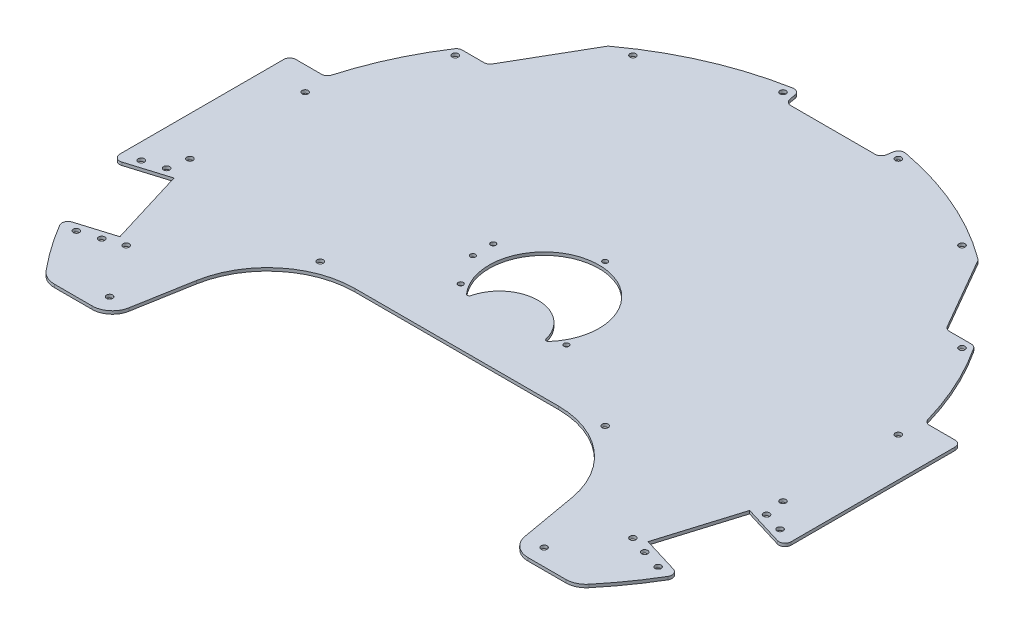
SolidWorks part; units mm, degrees
material "3.0205 (EN-AW 1200)"
ref_plane "Plan de face" through (0, 0, 0) normal (0, 0, 1) x (1, 0, 0)
ref_plane "Plan de dessus" through (0, 0, 0) normal (0, 1, 0) x (1, 0, 0)
ref_plane "Plan de droite" through (0, 0, 0) normal (1, 0, 0) x (0, 0, -1)
sketch "Esquisse1" plane through (0, 0, 0) normal (0, 1, 0) x (1, 0, 0)
  line L2 (0, 0) -> (165, 0) construction
  line L4 (165, -54.557) -> (165, 55.2417)
  line L5 (-165, 55.2417) -> (-104.5177, 160)
  line L6 (-165, -54.557) -> (-165, 55.2417)
  line L9 (0, 160) -> (0, 0) construction
  line L12 (-104.5177, 160) -> (104.5177, 160)
  line L13 (165, 55.2417) -> (104.5177, 160)
  arc A0 (-165, -54.557) -> (-112.9493, -132.0754) centre (0, 0) ccw
  circle A1 centre (158.5, 53.5) radius 6.5 construction
  circle A2 centre (-158.5, 53.5) radius 6.5 construction
  circle A3 centre (158.5, -53.5) radius 6.5 construction
  circle A4 centre (-158.5, -53.5) radius 6.5 construction
  arc A5 (-112.9493, -132.0754) -> (112.9493, -132.0754) centre (0, 355) ccw
  arc A6 (112.9493, -132.0754) -> (165, -54.557) centre (0, 0) ccw
  point P21 (0, -145)
  dimension "D2" = 145
  dimension "D13" = 225.8987
  dimension "D16" = 500
  dimension "D9" = 13
  dimension "D12" = 317
  dimension "D15" = 107
  dimension "D4" = 60
  dimension "D5" = 209.0355
  dimension "D6" = 330
  dimension "D7" = 120.9645
  dimension "D8" = 109.7986
  dimension "D10" = 93.3723
  dimension "D11" = 160
extrude "Boss.-Extru.1" add sketch "Esquisse1" along normal blind 1.5
sketch "Esquisse2" plane through (0, 1.5, 0) normal (0, 1, 0) x (1, 0, 0)
  line L0 (0, 0) -> (0, -145) construction
  line L1 (-92.3467, -78.5331) -> (-104.0666, -145)
  line L2 (-50, -43) -> (50, -43)
  line L3 (92.3467, -78.5331) -> (104.0666, -145)
  line L4 (-104.0666, -145) -> (104.0666, -145)
  line L5 (141.4855, -40.4511) -> (166.9803, -48.2251)
  line L6 (141.4855, -40.4511) -> (129.8189, -78.7119)
  line L7 (166.9803, -48.2251) -> (155.3137, -86.4859)
  line L8 (129.8189, -78.7119) -> (155.3137, -86.4859)
  line L9 (151.0507, -43.3677) -> (145.2174, -62.4981) construction
  line L10 (145.2174, -62.4981) -> (135.6522, -59.5815) construction
  line L11 (-141.4855, -40.4511) -> (-166.9803, -48.2251)
  line L12 (-166.9803, -48.2251) -> (-155.3137, -86.4859)
  line L13 (-141.4855, -40.4511) -> (-129.8189, -78.7119)
  line L14 (-129.8189, -78.7119) -> (-155.3137, -86.4859)
  line L15 (-106.7731, -106.7731) -> (0, 0) construction
  line L16 (165, -54.557) -> (165, 55.2417) construction
  arc A0 (18.8162, -19.3636) -> (-18.8162, -19.3636) centre (0, -22) ccw
  arc A1 (-50, -43) -> (-92.3467, -78.5331) centre (-50, -86) ccw
  arc A2 (-112.9493, -132.0754) -> (112.9493, -132.0754) centre (0, 355) ccw construction
  arc A3 (50, -43) -> (92.3467, -78.5331) centre (50, -86) cw
  arc A4 (18.8162, -19.3636) -> (-18.8162, -19.3636) centre (0, 0) ccw
  circle A5 centre (-106.7731, -106.7731) radius 1.5
  circle A6 centre (143, -86.913) radius 1.5
  circle A7 centre (133.4348, -83.9963) radius 1.5
  circle A8 centre (147.4348, -38.0833) radius 1.5
  circle A9 centre (157, -41) radius 1.5
  arc A10 (112.9493, -132.0754) -> (165, -54.557) centre (0, 0) ccw construction
  circle A11 centre (-147.4348, -38.0833) radius 1.5
  circle A12 centre (-157, -41) radius 1.5
  circle A13 centre (-143, -86.913) radius 1.5
  circle A14 centre (-133.4348, -83.9963) radius 1.5
  circle A15 centre (106.7731, -106.7731) radius 1.5
  dimension "D1" = 19
  dimension "D2" = 22
  dimension "D3" = 86
  dimension "D4" = 100
  dimension "D5" = 54
  dimension "D8" = 10
  dimension "D9" = 48
  dimension "D10" = 10
  dimension "D14" = 41
  dimension "D15" = 3
  dimension "D6" = 86
  dimension "D7" = 20
  dimension "D12" = 3
  dimension "D13" = 8
  dimension "D18" = 22
  dimension "D11" = 40
  dimension "D16" = 151
  dimension "D17" = 45
extrude "Enlèv. mat.-Extru.1" cut sketch "Esquisse2" against normal blind 10
sketch "Esquisse3" plane through (0, 1.5, 0) normal (0, 1, 0) x (1, 0, 0)
  line L1 (-130.2938, -115) -> (130.2938, -115)
  line L2 (-130.2938, -115) -> (-130.2938, -134.4427)
  line L3 (-130.2938, -134.4427) -> (130.2938, -134.4427)
  line L4 (130.2938, -115) -> (130.2938, -134.4427)
  arc A0 (-151.4132, -85.2965) -> (-112.9493, -132.0754) centre (0, 0) ccw construction
  arc A1 (112.9493, -132.0754) -> (151.4132, -85.2965) centre (0, 0) ccw construction
  circle A2 centre (-106.7731, -106.7731) radius 1.5 construction
  dimension "D1" = 8.2269
  dimension "D2" = 115
extrude "Enlèv. mat.-Extru.2" cut sketch "Esquisse3" against normal through all
fillet "Congé1" radius 10 8 edges at (130.2938, 0.75, 115) (98.7768, 0.75, 115) (-98.7768, 0.75, 115) (-130.2938, 0.75, 115) (165, 0.75, -55.2417) (104.5177, 0.75, -160) (-104.5177, 0.75, -160) (-165, 0.75, -55.2417)
fillet "Congé2" radius 1 2 edges at (18.8162, 0.75, 19.3636) (-18.8162, 0.75, 19.3636)
sketch "Esquisse4" plane through (0, 1.5, 0) normal (0, 1, 0) x (1, 0, 0)
  line L0 (0, 0) -> (-124.5426, -80.8789) construction
  line L1 (0, 0) -> (-145.7716, -28.3351) construction
  line L2 (0, 0) -> (-165, 0) construction
  line L3 (-165, 52.5622) -> (-165, -47.6212) construction
  circle A0 centre (-124.5426, -80.8789) radius 1.5
  circle A1 centre (-145.7716, -28.3351) radius 1.5
  circle A2 centre (-145.7716, 28.3351) radius 1.5
  circle A3 centre (-124.5426, 80.8789) radius 1.5
  dimension "D1" = 148.5
  dimension "D2" = 3
  dimension "D4" = 22
  dimension "D5" = 11
  dimension "D3" = 4
extrude "Enlèv. mat.-Extru.3" cut sketch "Esquisse4" against normal through all
pattern_circular "Répétition circulaire1" count 3 every 90 about axis through (0, 0, 0) along (0, 1, 0) of "Enlèv. mat.-Extru.3"
sketch "Esquisse5" plane through (0, 1.5, 0) normal (0, 1, 0) x (1, 0, 0)
  line L0 (0, 0) -> (0, 160) construction
  line L1 (98.7442, 160) -> (-98.7442, 160) construction
  line L2 (50, -43) -> (-50, -43) construction
  circle A0 centre (-70, -40) radius 1.5
  circle A1 centre (70, -40) radius 1.5
  dimension "D1" = 140
  dimension "D2" = 3
  dimension "D3" = 40
  dimension "D4" = 3
extrude "Enlèv. mat.-Extru.4" cut sketch "Esquisse5" against normal through all
sketch "Esquisse6" plane through (0, 1.5, 0) normal (0, 1, 0) x (1, 0, 0)
  line L0 (-165, 40) -> (-147.1606, 40)
  line L1 (-165, 52.5622) -> (-165, -47.6212) construction
  line L2 (147.1606, 40) -> (165, 40)
  line L3 (165, -47.6212) -> (165, 52.5622) construction
  line L4 (165, 40) -> (165, 160)
  line L5 (165, 160) -> (-165, 160)
  line L6 (-165, 160) -> (-165, 40)
  line L7 (98.7442, 160) -> (-98.7442, 160) construction
  arc A0 (-147.1606, 40) -> (147.1606, 40) centre (0, 0) cw
  circle A1 centre (-80.8789, 124.5426) radius 1.5 construction
  dimension "D1" = 4
  dimension "D3" = 152.5
  dimension "D2" = 40
extrude "Enlèv. mat.-Extru.5" cut sketch "Esquisse6" against normal through all
sketch "Esquisse7" plane through (0, 1.5, 0) normal (0, 1, 0) x (1, 0, 0)
  line L0 (126.6958, 122.3659) -> (126.6958, 84.8789)
  line L1 (126.6958, 122.3659) -> (91.0101, 122.3659)
  line L2 (126.6958, 84.8789) -> (112.6532, 84.8789)
  line L3 (91.0101, 122.3659) -> (112.6532, 84.8789)
  line L4 (0, 0) -> (0, 152.5) construction
  line L5 (-91.0101, 122.3659) -> (-112.6532, 84.8789)
  line L6 (-126.6958, 84.8789) -> (-112.6532, 84.8789)
  line L7 (-126.6958, 122.3659) -> (-91.0101, 122.3659)
  line L8 (-126.6958, 122.3659) -> (-126.6958, 84.8789)
  arc A0 (147.1606, 40) -> (-147.1606, 40) centre (0, 0) ccw construction
  arc A1 (147.1606, 40) -> (-147.1606, 40) centre (0, 0) ccw construction
  circle A3 centre (124.5426, 80.8789) radius 4 construction
  dimension "D3" = 30
  dimension "D7" = 140
extrude "Enlèv. mat.-Extru.6" cut sketch "Esquisse7" against normal through all
fillet "Congé3" radius 3 14 edges at (151.4132, 0.75, 85.2965) (165, 0.75, 47.6212) (-151.4132, 0.75, 85.2965) (-165, 0.75, 47.6212) (-165, 0.75, -40) (-147.1606, 0.75, -40) (147.1606, 0.75, -40) (165, 0.75, -40) (-126.6958, 0.75, -84.8789) (126.6958, 0.75, -84.8789) (91.0101, 0.75, -122.3659) (-91.0101, 0.75, -122.3659) (-112.6532, 0.75, -84.8789) (112.6532, 0.75, -84.8789)
sketch "Esquisse8" plane through (0, 1.5, 0) normal (0, 1, 0) x (1, 0, 0)
  circle A0 centre (-35, 0) radius 1.25
  circle A1 centre (-35, 10) radius 1.25
  circle A2 centre (0, 0) radius 30 construction
  circle A3 centre (0, 30) radius 1.25
  circle A4 centre (25.9808, -15) radius 1.25
  circle A5 centre (-25.9808, -15) radius 1.25
  dimension "D1" = 2.5
  dimension "D2" = 10
  dimension "D3" = 35
  dimension "D4" = 120
  dimension "D5" = 30
extrude "Enlèv. mat.-Extru.7" cut sketch "Esquisse8" against normal blind 4
sketch "Esquisse9" plane through (0, 1.5, 0) normal (0, 1, 0) x (1, 0, 0)
  line L1 (-25, 152.5) -> (25, 152.5)
  line L2 (-25, 152.5) -> (-23.2787, 142)
  line L3 (-23.2787, 142) -> (23.2787, 142)
  line L4 (25, 152.5) -> (23.2787, 142)
  arc A0 (90.5041, 122.7406) -> (-90.5041, 122.7406) centre (0, 0) ccw construction
  point P4 (0, 142)
  dimension "D1" = 50
  dimension "D2" = 142
extrude "Enlèv. mat.-Extru.8" cut sketch "Esquisse9" against normal through all
fillet "Congé4" radius 3 4 edges at (23.2787, 0.75, -142) (24.6707, 0.75, -150.4912) (-23.2787, 0.75, -142) (-24.6707, 0.75, -150.4912)
